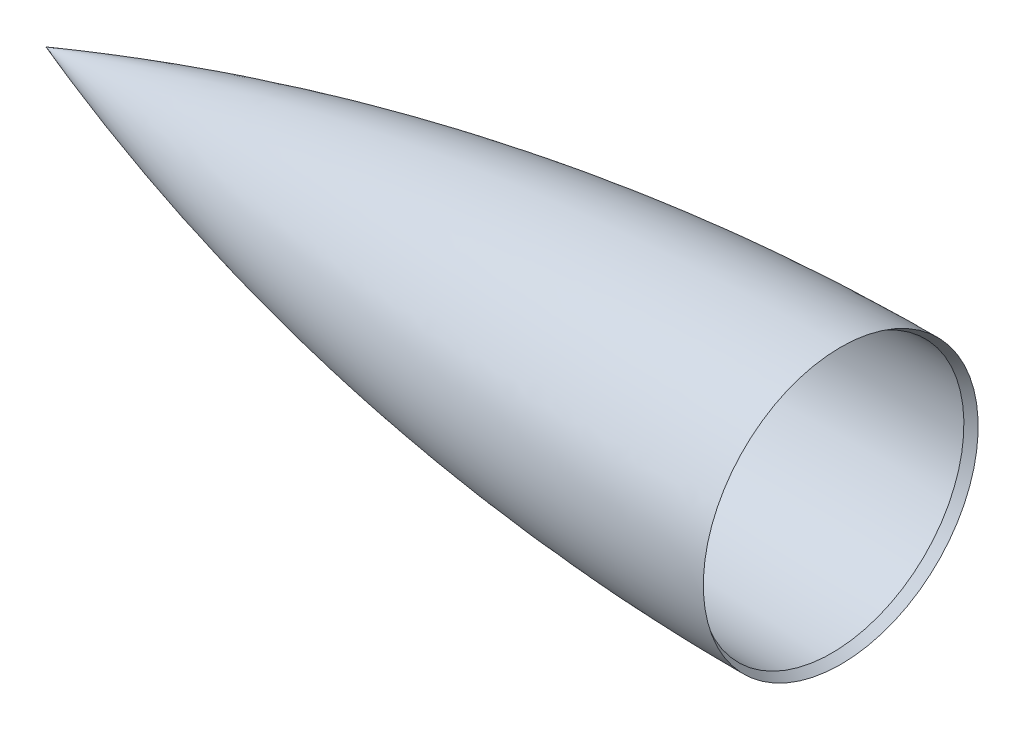
SolidWorks part; units mm, degrees
ref_plane "Front Plane" through (0, 0, 0) normal (0, 0, 1) x (1, 0, 0)
ref_plane "Top Plane" through (0, 0, 0) normal (0, 1, 0) x (1, 0, 0)
ref_plane "Right Plane" through (0, 0, 0) normal (1, 0, 0) x (0, 0, -1)
sketch "Sketch1" plane through (0, 0, 0) normal (0, 0, 1) x (1, 0, 0)
  line L0 (0, 0) -> (-229, 0) construction
  line L1 (0, 36.6) -> (0, -642.3338) construction
  line L3 (-229, 0) -> (-219.9054, 0)
  line L4 (83, 38.1) -> (2.5981, 38.1)
  line L7 (0, 39.6) -> (83, 39.6)
  line L8 (83, 38.1) -> (83, 39.6)
  line L9 (0, 36.6) -> (2.5981, 38.1)
  line L10 (0, 36.6) -> (119.7357, 36.6) construction
  line L11 (2.5981, 38.1) -> (119.7357, 38.1) construction
  line L12 (119.7357, 36.6) -> (119.7357, 38.1) construction
  line L13 (-79.2, 81.783) -> (-79.2, 33.475) construction
  line L15 (0, 39.6) -> (-2.6067, 38.095)
  line L16 (-79.2, 33.475) -> (-82.5018, 31.5687)
  line L17 (-79.2, 31.9647) -> (-79.2, -62.4632) construction
  circle A0 centre (0, -642.3338) radius 681.9338 construction
  arc A1 (-229, 0) -> (0, 39.6) centre (0, -642.3338) cw
  arc A2 (-219.9054, 0) -> (0, 36.6) centre (0, -642.3338) cw
  arc A3 (-227.9926, -2.8258) -> (0, 36.6) centre (0, -642.3338) cw construction
  arc A4 (-79.2, 33.475) -> (-2.6067, 38.095) centre (0, -642.3338) cw
  arc A5 (-220.3913, 1.4191) -> (0, 38.1) centre (0, -642.3338) cw construction
  point P0 (0, 39.6)
  dimension "D1" = 39.6
  dimension "D2" = 229
  dimension "D3" = 681.9338
  dimension "D5" = 83
  dimension "D6" = 1.5
  dimension "D7" = 30
  dimension "D8" = 80.4019
  dimension "D9" = 1.5
  dimension "D10" = 38.1
  dimension "D11" = 1.5
  dimension "D12" = 79.2
  dimension "D13" = 30
  dimension "D14" = 30
  dimension "D4" = 3
revolve "Revolve1" add sketch "Sketch1" angle 360 about L0
